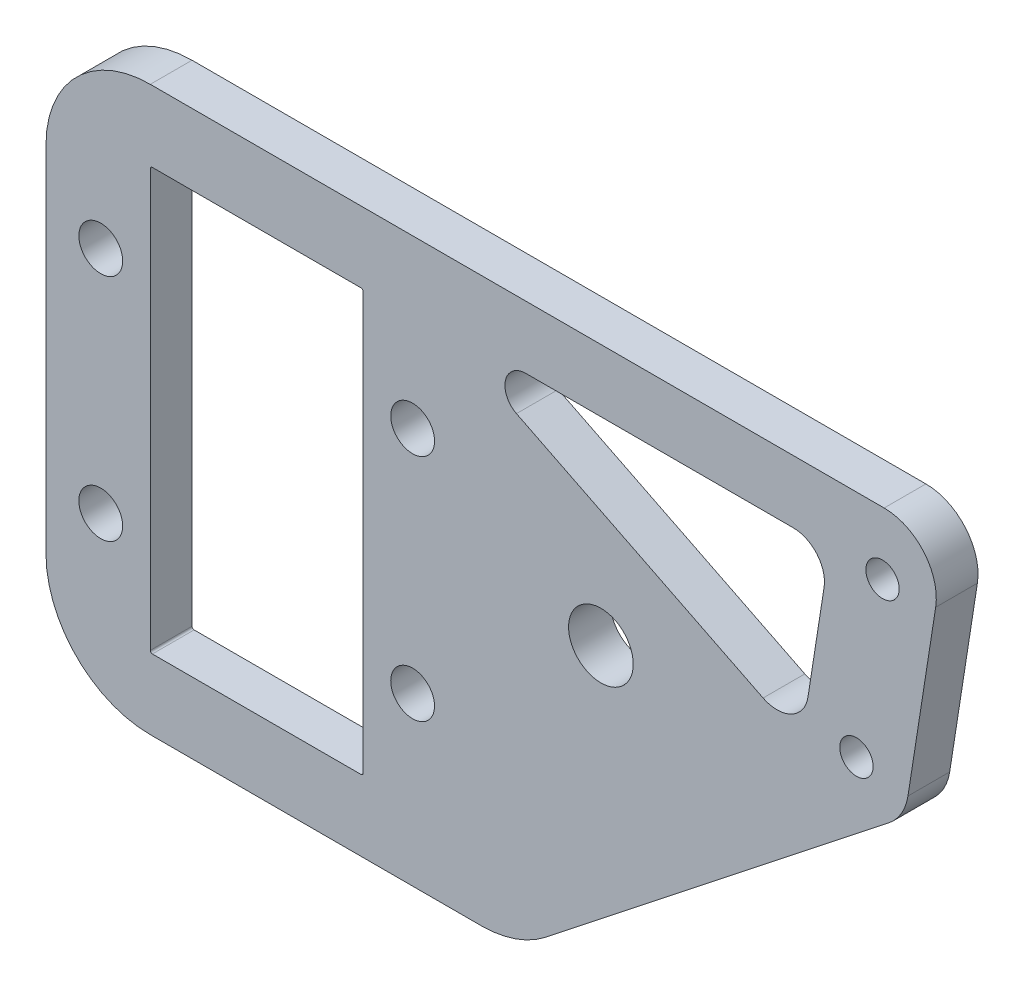
SolidWorks part; units mm, degrees
ref_plane "前视基准面" through (0, 0, 0) normal (0, 0, 1) x (1, 0, 0)
ref_plane "上视基准面" through (0, 0, 0) normal (0, 1, 0) x (1, 0, 0)
ref_plane "右视基准面" through (0, 0, 0) normal (1, 0, 0) x (0, 0, -1)
sketch "草图1" plane through (0, 0, 0) normal (0, 0, 1) x (1, 0, 0)
  line L0 (-10.2, 20.2) -> (10.2, 20.2)
  line L1 (-10, -20) -> (10, -20) construction
  line L2 (-10, -20) -> (-10, 20) construction
  line L3 (-10, 20) -> (10, 20) construction
  line L4 (10, -20) -> (10, 20) construction
  line L5 (-10, -20) -> (10, 20) construction
  line L6 (-10, 20) -> (10, -20) construction
  line L7 (10.2, -20.2) -> (10.2, 20.2)
  line L8 (-10.2, -20.2) -> (10.2, -20.2)
  line L9 (-10.2, -20.2) -> (-10.2, 20.2)
  line L10 (-10.2, 27) -> (60.1562, 27)
  line L11 (33, 25) -> (33, -25) construction
  line L12 (21.5311, -27) -> (-10.2, -27)
  line L13 (-20.2, -17) -> (-20.2, 17)
  line L15 (27.7237, -24.8519) -> (60.5963, 1.0741)
  line L16 (62.4401, 4.2281) -> (65.0963, 21.2281)
  circle A0 centre (33, 2) radius 3.1
  arc A1 (-10.2, -27) -> (-20.2, -17) centre (-10.2, -17) cw
  arc A2 (-10.2, 27) -> (-20.2, 17) centre (-10.2, 17) ccw
  circle A6 centre (33, 2) radius 12.5 construction
  circle A9 centre (60, 21) radius 1.6
  circle A10 centre (57.5, 5) radius 1.6
  arc A12 (60.5963, 1.0741) -> (62.4401, 4.2281) centre (57.5, 5) ccw
  arc A13 (21.5311, -27) -> (27.7237, -24.8519) centre (21.5311, -17) ccw
  arc A14 (65.0963, 21.2281) -> (60.1562, 27) centre (60.1562, 22) ccw
  point P0 (0, 0)
  point P32 (25, -27)
  dimension "D8" = 6.2
  dimension "D10" = 10
  dimension "D11" = 3.2
  dimension "D12" = 19
  dimension "D13" = 25
  dimension "D9" = 25
  dimension "D14" = 27
  dimension "D15" = 3.2
  dimension "D18" = 10
  dimension "D20" = 10
  dimension "D21" = 5
  dimension "D1" = 40
  dimension "D2" = 20
  dimension "D3" = 0.2
  dimension "D4" = 7
  dimension "D5" = 7
  dimension "D6" = 10
  dimension "D7" = 43
  dimension "D16" = 3
  dimension "D17" = 24.5
  dimension "D19" = 25
  dimension "D22" = 5
extrude "凸台-拉伸1" add sketch "草图1" along normal blind 4
fillet "圆角1" radius 0.2 4 edges at (10.2, -20.2, 2) (-10.2, -20.2, 2) (-10.2, 20.2, 2) (10.2, 20.2, 2)
sketch "草图2" plane through (0, 0, 4) normal (0, 0, 1) x (1, 0, 0)
  line L0 (14.95, 11) -> (14.95, -11) construction
  line L1 (9.95, 20.25) -> (9.95, -49979.75) construction
  line L2 (0, 0) -> (50000, 0) construction
  line L3 (10.2, -20) -> (10.2, 20) construction
  line L4 (0, 0.6321) -> (0, 50000.6321) construction
  line L5 (-14.95, 11) -> (-14.95, -11) construction
  circle A0 centre (14.95, 11) radius 2.1
  circle A4 centre (14.95, -11) radius 2.1
  circle A5 centre (-14.95, -11) radius 2.1
  circle A6 centre (-14.95, 11) radius 2.1
  dimension "D1" = 4.2
  dimension "D2" = 22
  dimension "D4" = 0.25
  dimension "D5" = 5
extrude "切除-拉伸1" cut sketch "草图2" against normal blind 4
sketch "草图3" plane through (0, 0, 4) normal (0, 0, 1) x (1, 0, 0)
  line L0 (25.798, 21) -> (51.4342, 21)
  line L1 (54.3982, 17.5369) -> (52.8522, 7.6426)
  line L2 (48.5495, 5.4209) -> (24.9056, 17.2102)
  line L3 (60.1562, 27) -> (-10.2, 27) construction
  line L4 (14.95, 11) -> (33, 2) construction
  line L5 (57.5, 5) -> (60, 21) construction
  line L6 (62.4401, 4.2281) -> (65.0963, 21.2281) construction
  arc A0 (54.3982, 17.5369) -> (51.4342, 21) centre (51.4342, 18) ccw
  arc A1 (24.9056, 17.2102) -> (25.798, 21) centre (25.798, 19) cw
  arc A2 (48.5495, 5.4209) -> (52.8522, 7.6426) centre (49.8882, 8.1057) ccw
  dimension "3" = 3
  dimension "D2" = 2
  dimension "D3" = 3
  dimension "D1" = 6
  dimension "D4" = 10
  dimension "D5" = 10
extrude "切除-拉伸2" cut sketch "草图3" against normal blind 10
equation "\"4。2\"=3.2"
equation "\"6。2\"=6.5866"
equation "\"3。2\"=6.2"
equation "\"12。5\"=10"
